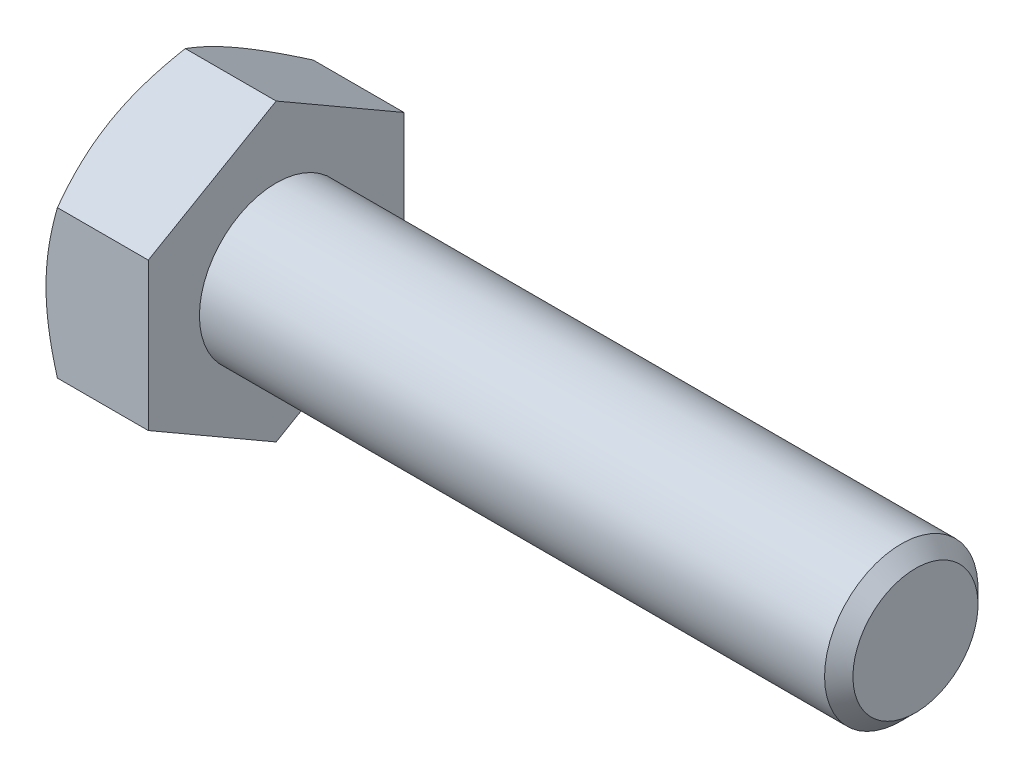
SolidWorks part; units mm, degrees
ref_plane "Plane1" through (0, 0, 0) normal (0, 0, 1) x (1, 0, 0)
ref_plane "Plane2" through (0, 0, 0) normal (0, 1, 0) x (1, 0, 0)
ref_plane "Plane3" through (0, 0, 0) normal (1, 0, 0) x (0, 0, -1)
sketch "Sketch1" plane through (0, 0, 0) normal (1, 0, 0) x (0, 0, -1)
  line L0 (5, 2.8868) -> (5, -2.8868)
  line L1 (-5, 2.8868) -> (-5, -2.8868)
  line L2 (5, -2.8868) -> (0, -5.7735)
  line L3 (0, -5.7735) -> (-5, -2.8868)
  line L4 (5, 2.8868) -> (0, 5.7735)
  line L5 (0, 5.7735) -> (-5, 2.8868)
  dimension "Width_flats" = 10
  dimension "D2" = 120
  dimension "D3" = 5
  dimension "D4" = 5
  dimension "D5" = 5
extrude "BaseHead" add sketch "Sketch1" along normal blind 4
sketch "BodySke" plane through (0, 0, 0) normal (0, 0, 1) x (1, 0, 0)
  line L1 (0, 0) -> (29, 0)
  line L2 (0, 0) -> (0, 3)
  line L4 (29, 0) -> (29, 2.4455)
  line L5 (4, 5.7735) -> (4, 2.8868) construction
  line L6 (29, 2.4455) -> (28.4455, 3)
  line L7 (0, 0) -> (110.49, 0) construction
  line L8 (29, -2.4455) -> (28.4455, -3) construction
  line L9 (0, 2.8868) -> (0, -2.8868) construction
  line L10 (5, 15.24) -> (5, -1.27) construction
  line L11 (11, 15.24) -> (11, -1.27) construction
  line L12 (4, 2.8868) -> (4, -2.8868) construction
  line L15 (0, 3) -> (28.4455, 3)
  dimension "Length" = 25
  dimension "Body_ch_ang" = 45
  dimension "Diameter" = 6
  dimension "Minor_dia" = 4.891
  dimension "Advance" = 1
  dimension "Thread_nom" = 18
revolve "BaseBody" add sketch "BodySke" angle 360 about L7
cosmetic thread "ThreadCosmetic" parameters "Thread_length"=18, "Thread_minor"=4.891
fillet "HeadFillet" [suppressed] radius 0.25
sketch "Sketch3" plane through (0, 0, 0) normal (0, 0, 1) x (1, 0, 0)
  line L0 (0, 5) -> (3.3333, 10.7735)
  line L1 (0, 5.7735) -> (0, 2.8868) construction
  line L2 (3.3333, 10.7735) -> (3.3333, 15.7735)
  line L3 (3.3333, 15.7735) -> (-10, 15.7735)
  line L4 (-10, 15.7735) -> (-10, 5)
  line L5 (-10, 5) -> (0, 5)
  line L6 (0, 0) -> (99.06, 0) construction
  line L7 (4, 5.7735) -> (0, 5.7735) construction
  dimension "D1" = 5
  dimension "D2" = 5
  dimension "D3" = 10
  dimension "D4" = 5
  dimension "Head_ch_ang" = 30
revolve "HeadChamfer" cut sketch "Sketch3" angle 360 about L6
sketch "ThdSchSke" plane through (0, 0, 0) normal (0, 0, 1) x (1, 0, 0)
  line L0 (11, -2.4455) -> (10.6117, -3)
  line L1 (11, -2.4455) -> (11.3883, -3)
  line L2 (11.3883, -3) -> (11.3883, -3.75)
  line L3 (-3.175, 0) -> (5.1513, 0) construction
  line L5 (11.3883, -3.75) -> (10.6117, -3.75)
  line L6 (10.6117, -3.75) -> (10.6117, -3)
  dimension "Thread_minor" = 4.891
  dimension "Diameter" = 6
  dimension "Start" = 11
  dimension "SideAngle" = 55
  dimension "VeeAngle" = 70
  dimension "Overcut" = 7.5
revolve "ThreadSchematic" [suppressed] cut sketch "ThdSchSke" angle 360 about L3
pattern_linear "ThdSchPat" [suppressed]
equation "\"D3@Sketch1\" = \"Width_flats@Sketch1\" / 2"
equation "\"D4@Sketch1\" = \"D3@Sketch1\""
equation "\"D5@Sketch1\" = \"D4@Sketch1\""
equation "\"Thread_minor@ThreadCosmetic\" = \"Minor_dia@BodySke\""
equation "\"D1@Sketch3\" = \"Width_flats@Sketch1\" / 2"
equation "\"Thread_length@ThreadCosmetic\" = ((sgn( (\"Length@BodySke\" - \"Advance@BodySke\" ) - \"Thread_nom@BodySke\" )-1)*( (\"Length@BodySke\" - \"Advance@BodySke\" ) - \"Thread_nom@BodySke\" ))/-2+ \"Thread_nom@BodySke\""
equation "\"Thread_minor@ThdSchSke\" = \"Minor_dia@BodySke\""
equation "\"Diameter@ThdSchSke\" = \"Diameter@BodySke\""
equation "\"Overcut@ThdSchSke\" = \"Diameter@BodySke\" * 1.25"
equation "\"Start@ThdSchSke\" = \"Head_ht@BaseHead\" + \"Length@BodySke\" - \"Thread_length@ThreadCosmetic\"  '---Non-countersunk---"
equation "\"Num_threads@ThdSchPat\" = int( \"Thread_length@ThreadCosmetic\" / \"Advance@BodySke\" + 0.999 )  + 1"
equation "\"Advance@ThdSchPat\" = \"Thread_length@ThreadCosmetic\" /  (\"Num_threads@ThdSchPat\" - 1) 'relax it"
equation "\"Num_threads@ThdSchPat\" = \"Num_threads@ThdSchPat\" - sgn( \"Num_threads@ThdSchPat\" - 1) '---chamfered tips only---"
